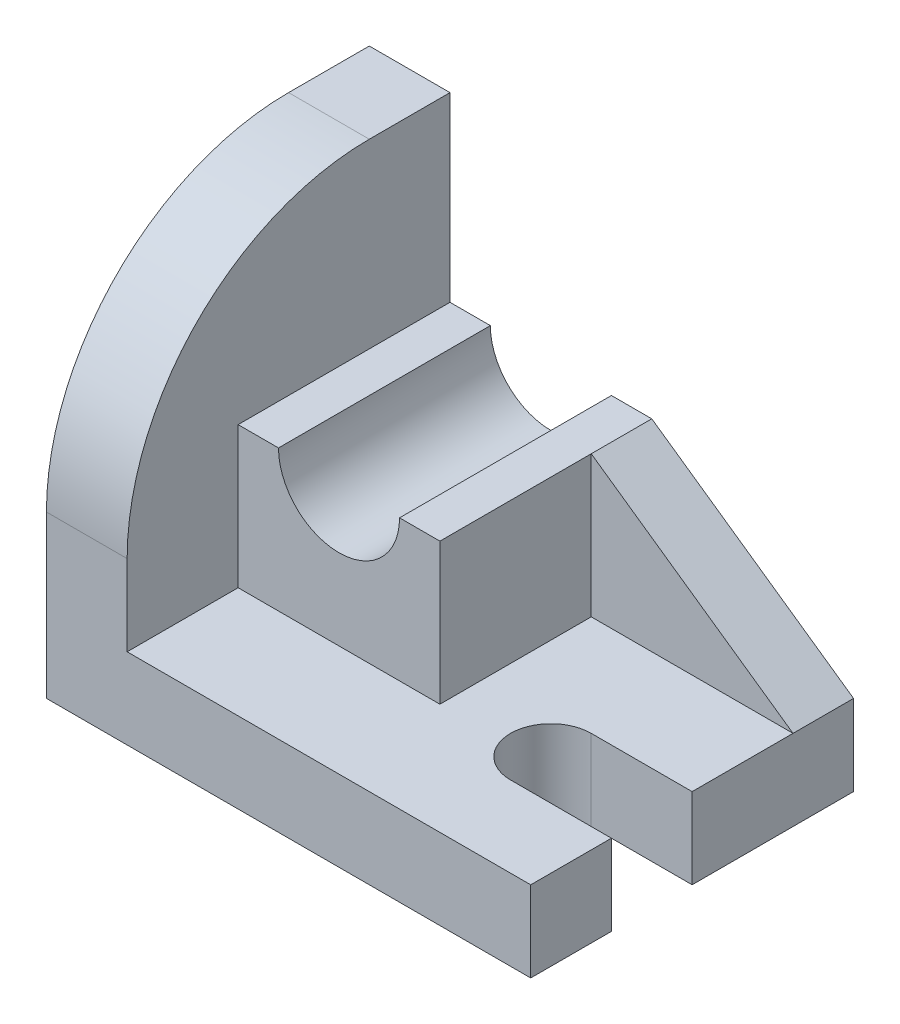
SolidWorks part; units mm, degrees
ref_plane "Front Plane" through (0, 0, 0) normal (0, 0, 1) x (1, 0, 0)
ref_plane "Top Plane" through (0, 0, 0) normal (0, 1, 0) x (1, 0, 0)
ref_plane "Right Plane" through (0, 0, 0) normal (1, 0, 0) x (0, 0, -1)
sketch "Sketch1" plane through (0, 0, 0) normal (0, 1, 0) x (1, 0, 0)
  line L1 (-48, 32) -> (48, 32)
  line L2 (-48, 32) -> (-48, -32)
  line L3 (-48, -32) -> (48, -32)
  line L4 (48, 32) -> (48, -32)
  line L5 (-48, 32) -> (48, -32) construction
  line L6 (-48, -32) -> (48, 32) construction
  point P0 (0, 0)
  dimension "D1" = 96
  dimension "D2" = 64
extrude "Boss-Extrude1" add sketch "Sketch1" along normal blind 16
sketch "Sketch2" plane through (-48, 0, 0) normal (-1, 0, 0) x (0, 0, 1)
  line L1 (-32, 16) -> (32, 16)
  line L2 (-32, 16) -> (-32, 80)
  line L3 (-32, 80) -> (32, 80)
  line L4 (32, 16) -> (32, 80)
  dimension "D1" = 64
  dimension "D2" = 64
extrude "Boss-Extrude2" add sketch "Sketch2" against normal blind 16
fillet "Fillet2" radius 48 1 edges at (-40, 80, 32)
sketch "Sketch3" plane through (0, 16, 0) normal (0, 1, 0) x (1, 0, 0)
  line L0 (-32, -32) -> (48, -32) construction
  line L1 (-32, 32) -> (8, 32)
  line L2 (-32, 32) -> (-32, -10)
  line L3 (-32, -10) -> (8, -10)
  line L4 (8, 32) -> (8, -10)
  dimension "D1" = 22
  dimension "D2" = 40
extrude "Boss-Extrude3" add sketch "Sketch3" along normal blind 28
sketch "Sketch4" plane through (0, 0, 10) normal (0, 0, 1) x (1, 0, 0)
  line L0 (8, 44) -> (8, 16) construction
  line L1 (-32, 44) -> (8, 44) construction
  circle A0 centre (-12, 44) radius 12
  dimension "D1" = 24
  dimension "D2" = 20
  dimension "D3" = 0
extrude "Cut-Extrude1" cut sketch "Sketch4" against normal through all
sketch "Sketch6" plane through (0, 16, 0) normal (0, 1, 0) x (1, 0, 0)
  line L0 (48, -8) -> (28, -8) construction
  line L1 (48, -32) -> (48, 32) construction
  line L2 (48, -16) -> (28, -16)
  line L3 (48, 0) -> (28, 0)
  line L4 (-32, -32) -> (48, -32) construction
  arc A0 (48, -16) -> (48, 0) centre (48, -8) ccw
  arc A1 (28, 0) -> (28, -16) centre (28, -8) ccw
  point P4 (38, -8)
  dimension "D1" = 16
  dimension "D2" = 16
  dimension "D3" = 20
extrude "Cut-Extrude2" cut sketch "Sketch6" against normal through all
sketch "Sketch7" plane through (0, 0, -32) normal (0, 0, -1) x (-1, 0, 0)
  line L0 (-8, 44) -> (-48, 16)
  line L10 (32, 44) -> (24, 44)
  line L11 (0, 44) -> (-8, 44)
  line L12 (-8, 44) -> (-8, 16)
  line L13 (-8, 16) -> (-48, 16)
  line L14 (-48, 16) -> (-48, 0)
  line L15 (-48, 0) -> (48, 0)
  line L16 (48, 0) -> (48, 80)
  line L17 (48, 80) -> (32, 80)
  line L18 (32, 80) -> (32, 44)
  line L21 (-8, 44) -> (-8, 16)
  line L22 (-8, 16) -> (-48, 16)
  arc A1 (0, 44) -> (24, 44) centre (12, 44) ccw
  dimension "D1" = 0
extrude "Boss-Extrude5" add sketch "Sketch7" against normal blind 12
